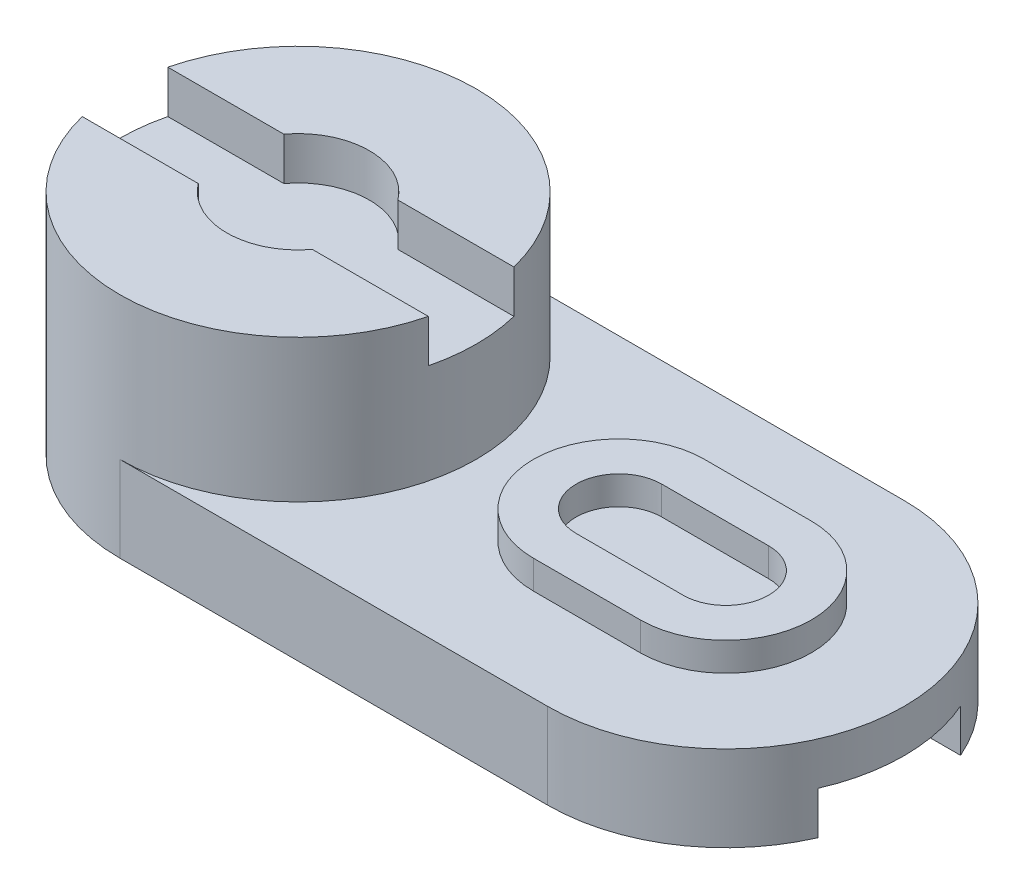
SolidWorks part; units mm, degrees
ref_plane "Front Plane" through (0, 0, 0) normal (0, 0, 1) x (1, 0, 0)
ref_plane "Top Plane" through (0, 0, 0) normal (0, 1, 0) x (1, 0, 0)
ref_plane "Right Plane" through (0, 0, 0) normal (1, 0, 0) x (0, 0, -1)
sketch "Sketch1" plane through (0, 0, 0) normal (0, 1, 0) x (1, 0, 0)
  line L0 (-30, 0) -> (30, 0) construction
  line L1 (-30, 25) -> (30, 25)
  line L2 (-30, -25) -> (30, -25)
  arc A0 (-30, 25) -> (-30, -25) centre (-30, 0) ccw
  arc A1 (30, -25) -> (30, 25) centre (30, 0) ccw
  point P2 (0, 0)
  dimension "D1" = 25
  dimension "D2" = 60
extrude "Boss-Extrude1" add sketch "Sketch1" along normal blind 12
sketch "Sketch2" plane through (0, 12, 0) normal (0, 1, 0) x (1, 0, 0)
  circle A0 centre (-30, 0) radius 25
extrude "Boss-Extrude2" add sketch "Sketch2" along normal blind 20
sketch "Sketch3" plane through (0, 12, 0) normal (0, 1, 0) x (1, 0, 0)
  line L0 (30, 0) -> (15, 0) construction
  line L1 (30, -12) -> (15, -12)
  line L2 (30, 12) -> (15, 12)
  line L3 (30, 0) -> (15, 0) construction
  line L4 (30, -6) -> (15, -6)
  line L5 (30, 6) -> (15, 6)
  arc A0 (30, -12) -> (30, 12) centre (30, 0) ccw
  arc A1 (15, 12) -> (15, -12) centre (15, 0) ccw
  arc A2 (30, -6) -> (30, 6) centre (30, 0) ccw
  arc A3 (15, 6) -> (15, -6) centre (15, 0) ccw
  point P4 (22.5, 0)
  point P11 (22.5, 0)
  dimension "D1" = 12
  dimension "D2" = 6
  dimension "D3" = 15
extrude "Boss-Extrude3" add sketch "Sketch3" along normal blind 4
sketch "Sketch4" plane through (0, 32, 0) normal (0, 1, 0) x (1, 0, 0)
  line L1 (-57.5, 6) -> (-2.5, 6)
  line L2 (-57.5, 6) -> (-57.5, -6)
  line L3 (-57.5, -6) -> (-2.5, -6)
  line L4 (-2.5, 6) -> (-2.5, -6)
  line L5 (-57.5, 6) -> (-2.5, -6) construction
  line L6 (-57.5, -6) -> (-2.5, 6) construction
  point P0 (-30, 0)
  dimension "D1" = 12
  dimension "D2" = 55
extrude "Cut-Extrude1" cut sketch "Sketch4" against normal blind 6
sketch "Sketch5" plane through (0, 26, 0) normal (0, 1, 0) x (1, 0, 0)
  circle A0 centre (-30, 0) radius 10
  dimension "D1" = 20
extrude "Cut-Extrude2" cut sketch "Sketch5" along normal blind 17
sketch "Sketch6" plane through (0, 0, 0) normal (0, -1, 0) x (1, 0, 0)
  line L1 (-62.5, 10) -> (62.5, 10)
  line L2 (-62.5, 10) -> (-62.5, -10)
  line L3 (-62.5, -10) -> (62.5, -10)
  line L4 (62.5, 10) -> (62.5, -10)
  line L5 (-62.5, 10) -> (62.5, -10) construction
  line L6 (-62.5, -10) -> (62.5, 10) construction
  point P0 (0, 0)
  dimension "D1" = 20
  dimension "D2" = 125
extrude "Cut-Extrude3" cut sketch "Sketch6" against normal blind 6
